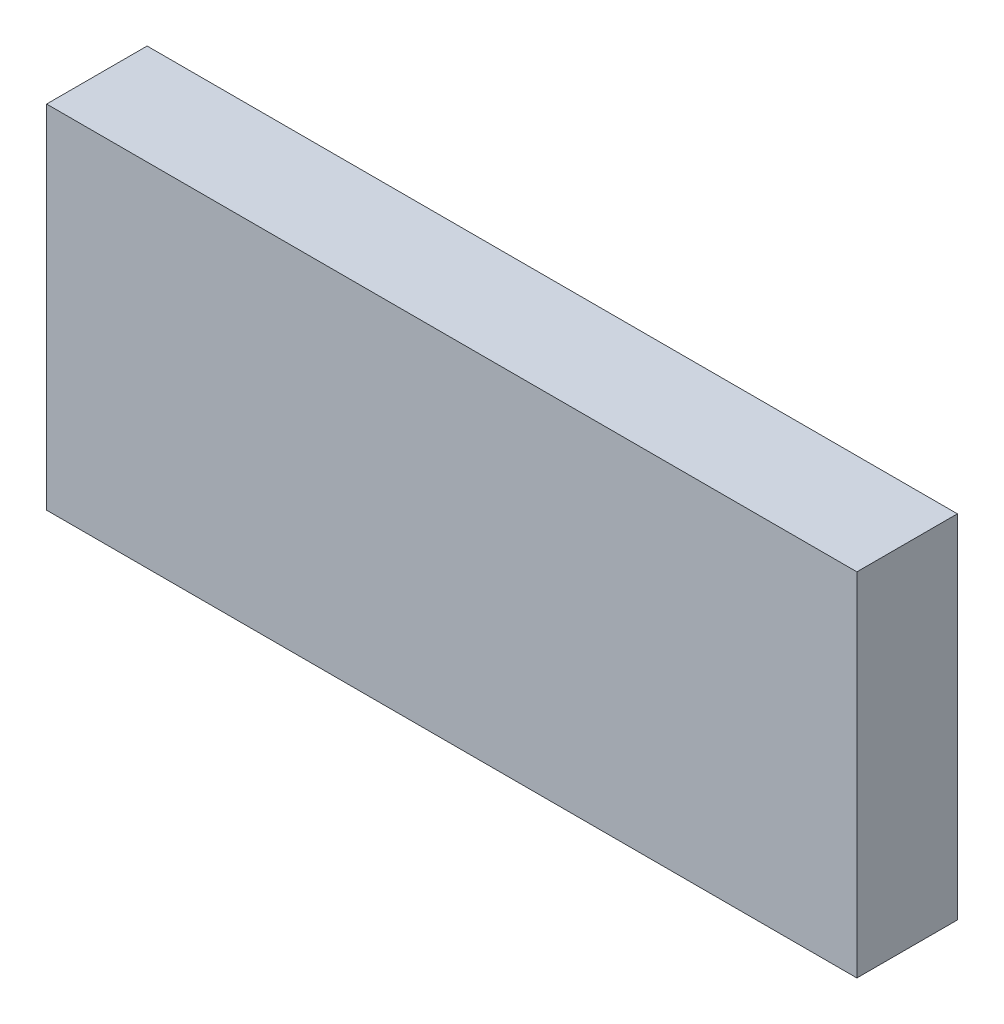
SolidWorks part; units mm, degrees
ref_plane "Front Plane" through (0, 0, 0) normal (0, 0, 1) x (1, 0, 0)
ref_plane "Top Plane" through (0, 0, 0) normal (0, 1, 0) x (1, 0, 0)
ref_plane "Right Plane" through (0, 0, 0) normal (1, 0, 0) x (0, 0, -1)
sketch "Sketch1" plane through (0, 0, 0) normal (0, 0, 1) x (1, 0, 0)
  line L1 (-409.575, -177.8) -> (409.575, -177.8)
  line L2 (-409.575, -177.8) -> (-409.575, 177.8)
  line L3 (-409.575, 177.8) -> (409.575, 177.8)
  line L4 (409.575, -177.8) -> (409.575, 177.8)
  line L5 (-409.575, -177.8) -> (409.575, 177.8) construction
  line L6 (-409.575, 177.8) -> (409.575, -177.8) construction
  point P0 (0, 0)
extrude "Boss-Extrude1" add sketch "Sketch1" along normal blind 101.6
